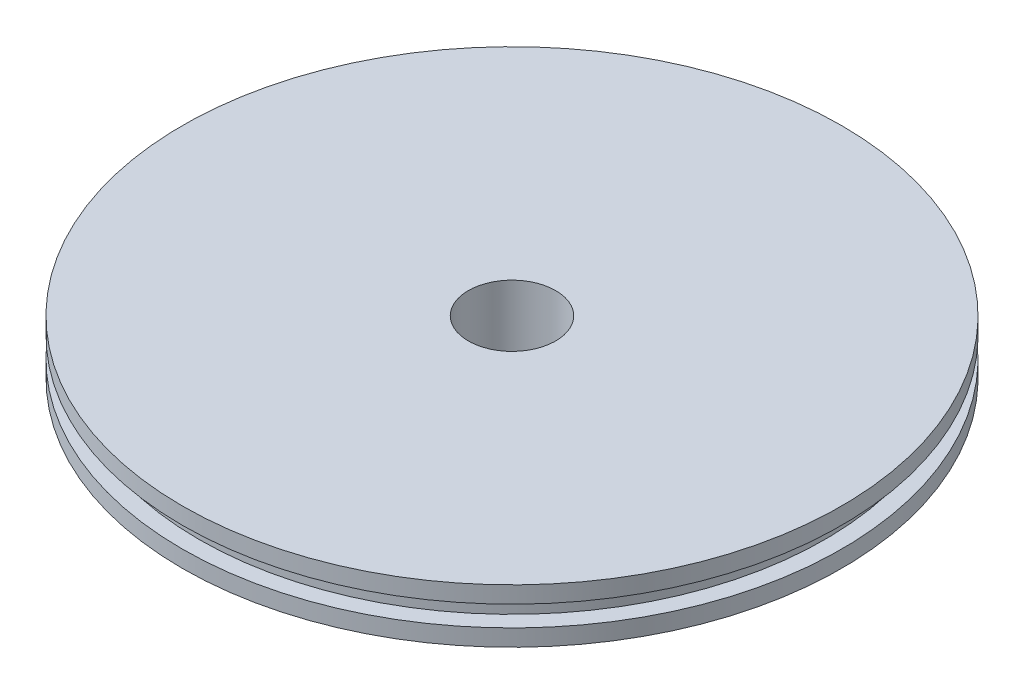
SolidWorks part; units mm, degrees
material "6061-T6 (SS)"
ref_plane "X-Y Datum" through (0, 0, 0) normal (0, 0, 1) x (1, 0, 0)
ref_plane "X-Z Datum" through (0, 0, 0) normal (0, 1, 0) x (1, 0, 0)
ref_plane "Y-Z Datum" through (0, 0, 0) normal (1, 0, 0) x (0, 0, -1)
sketch "Sketch1" plane through (0, 0, 0) normal (1, 0, 0) x (0, 0, -1)
  line L0 (0, 0) -> (0, -32027.2037) construction
  line L1 (0, 0) -> (0, -5.08)
  line L2 (0, -5.08) -> (-30.9499, -5.08)
  line L3 (-30.9499, -5.08) -> (-30.9499, -3.5052)
  line L4 (-30.9499, -3.5052) -> (-29.3878, -3.5052)
  line L5 (-29.3878, -3.5052) -> (-29.3878, -1.5748)
  line L6 (-29.3878, -1.5748) -> (-30.9499, -1.5748)
  line L7 (-30.9499, -1.5748) -> (-30.9499, 0)
  line L8 (-30.9499, 0) -> (0, 0)
  dimension "D1" = 61.8998
  dimension "D2" = 5.08
  dimension "D3" = 1.9304
  dimension "D5" = 58.7756
revolve "Revolve1" add sketch "Sketch1" angle 360 about L0
sketch "Sketch2" plane through (0, 0, 0) normal (0, 1, 0) x (1, 0, 0)
  circle A0 centre (0, 0) radius 19.05
  dimension "D1" = 38.1
split line "Split Line1" [suppressed]
sketch "Sketch3" [suppressed] plane through (0, 0, 0) normal (0, 1, 0) x (1, 0, 0)
  circle A0 centre (0, 0) radius 21.59
  dimension "D1" = 43.18
split line "Split Line2" [suppressed]
hole_wizard "Ø10.0mm Dowel Hole1" [suppressed] positions "Sketch4" profile "Sketch5" hole size "Ø10.0" standard "ANSI Metric"
sketch "Sketch4" [suppressed] plane through (0, 0, 0) normal (0, 1, 0) x (1, 0, 0)
  point P0 (0, 0)
sketch "Sketch5" plane through (0, 0, 0) normal (1, 0, 0) x (0, 0, 1)
  line L0 (0, 0) -> (0, 5.08)
  line L1 (0, 5.08) -> (5, 5.08)
  line L2 (5, 5.08) -> (5, 0)
  line L5 (5, 0) -> (0, 0)
  line L11 (0, -6.35) -> (0, 107.95) construction
  dimension "Thru Hole Dia." = 10
  dimension "Thru Hole Depth" = 5.08
sketch "Sketch6" plane through (0, -5.08, 0) normal (0, -1, 0) x (1, 0, 0)
  circle A0 centre (0, 0) radius 4.1021
  dimension "D1" = 8.2042
extrude "5/16 Close Fit hole" cut sketch "Sketch6" against normal through all
sketch "Sketch7" plane through (0, -5.08, 0) normal (0, -1, 0) x (1, 0, 0)
  circle A0 centre (0, 0) radius 22.86
  circle A1 centre (0, 0) radius 4.1021
  circle A2 centre (0, 0) radius 4.1021 construction
  dimension "D1" = 45.72
extrude "Boss-Extrude1" add sketch "Sketch7" along normal blind 1.016
